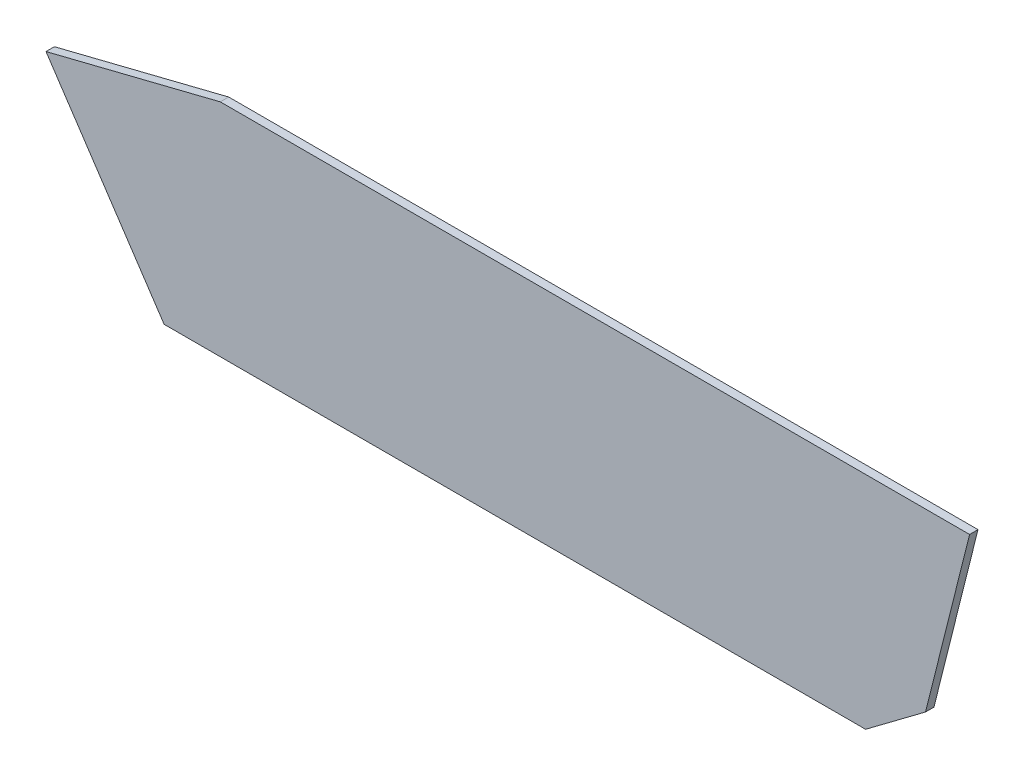
SolidWorks part; units mm, degrees
material "5052-H32"
ref_plane "Front Plane" through (0, 0, 0) normal (0, 0, 1) x (1, 0, 0)
ref_plane "Top Plane" through (0, 0, 0) normal (0, 1, 0) x (1, 0, 0)
ref_plane "Right Plane" through (0, 0, 0) normal (1, 0, 0) x (0, 0, -1)
sketch "Sketch1" plane through (0, 0, 0) normal (0, 0, 1) x (1, 0, 0)
  line L1 (425, 33.3333) -> (425, 28.5708)
  line L3 (425, 28.5708) -> (0, 28.5708)
  line L4 (0, 28.5708) -> (-98.8794, 3.851)
  line L6 (-98.8794, 3.851) -> (-31.8794, -96.649)
  line L7 (425, 28.5708) -> (400, -71.149)
  line L9 (400, -71.149) -> (366, -96.649)
  line L10 (-31.8794, -96.649) -> (366, -96.649)
  circle A0 centre (16, -83.899) radius 6.5
  circle A1 centre (80, -83.899) radius 6.5
  circle A2 centre (144, -83.899) radius 6.5
  circle A3 centre (208, -83.899) radius 6.5
  circle A4 centre (272, -83.899) radius 6.5
  circle A5 centre (336, -83.899) radius 6.5
  point P0 (-48.8794, -71.149)
  point P2 (-31.8794, -96.649)
  point P9 (400, -71.149)
  point P23 (0, 0)
  point P24 (0, 0)
  point P25 (0, 0)
  dimension "D4" = 64
  dimension "D1" = 25.5
  dimension "D3" = 75
  dimension "D5" = 25
  dimension "D6" = 64
  dimension "D7" = 523.8794
  dimension "D8" = 64
  dimension "D9" = 64
  dimension "D10" = 64
  dimension "D11" = 64
extrude "Boss-Extrude1" add sketch "Sketch1" along normal blind 4.7625 contours L3 L4 L6 L10 L9 L7
